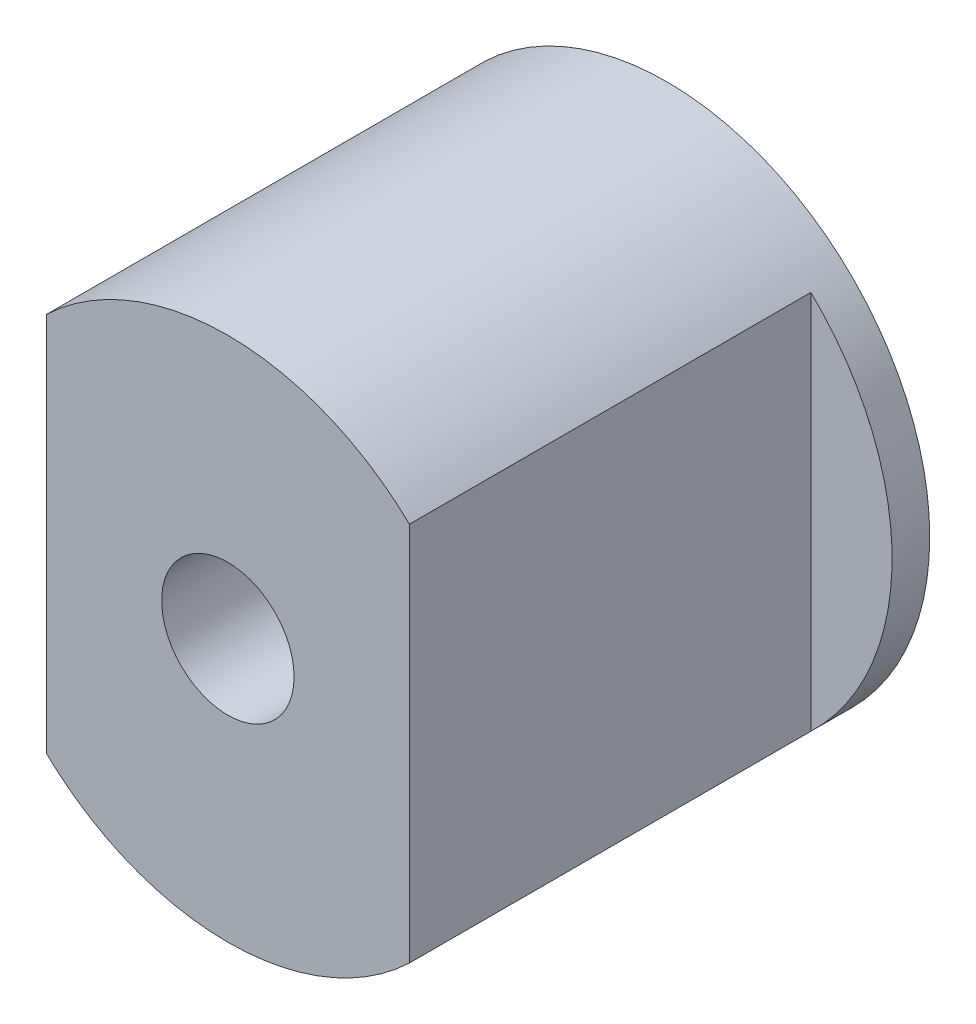
SolidWorks part; units mm, degrees
ref_plane "Front" through (0, 0, 0) normal (0, 0, 1) x (1, 0, 0)
ref_plane "Top" through (0, 0, 0) normal (0, 1, 0) x (1, 0, 0)
ref_plane "Right" through (0, 0, 0) normal (1, 0, 0) x (0, 0, -1)
sketch "Sketch1" plane through (0, 0, 0) normal (0, 0, 1) x (1, 0, 0)
  circle A0 centre (0, 0) radius 3.4925
  dimension "D1" = 6.985
extrude "Extrude1" add sketch "Sketch1" along normal blind 0.5
sketch "Sketch2" plane through (0, 0, 0.5) normal (0, 0, 1) x (1, 0, 0)
  line L0 (0, -3.667) -> (0, 3.8813) construction
  line L1 (2.413, -2.5249) -> (2.413, 2.5249)
  line L2 (-2.413, -2.5249) -> (-2.413, 2.5249)
  circle A0 centre (0, 0) radius 3.4925 construction
  arc A1 (2.413, 2.5249) -> (-2.413, 2.5249) centre (0, 0) ccw
  arc A2 (-2.413, -2.5249) -> (2.413, -2.5249) centre (0, 0) ccw
  dimension "D1" = 2.413
  dimension "D2" = 2.413
extrude "Extrude2" add sketch "Sketch2" along normal blind 5.334
sketch "Sketch3" plane through (0, 0, 5.834) normal (0, 0, 1) x (1, 0, 0)
  circle A0 centre (0, 0) radius 0.88
extrude "Cut-Extrude1" cut sketch "Sketch3" against normal up to surface (5.834 mm away)
